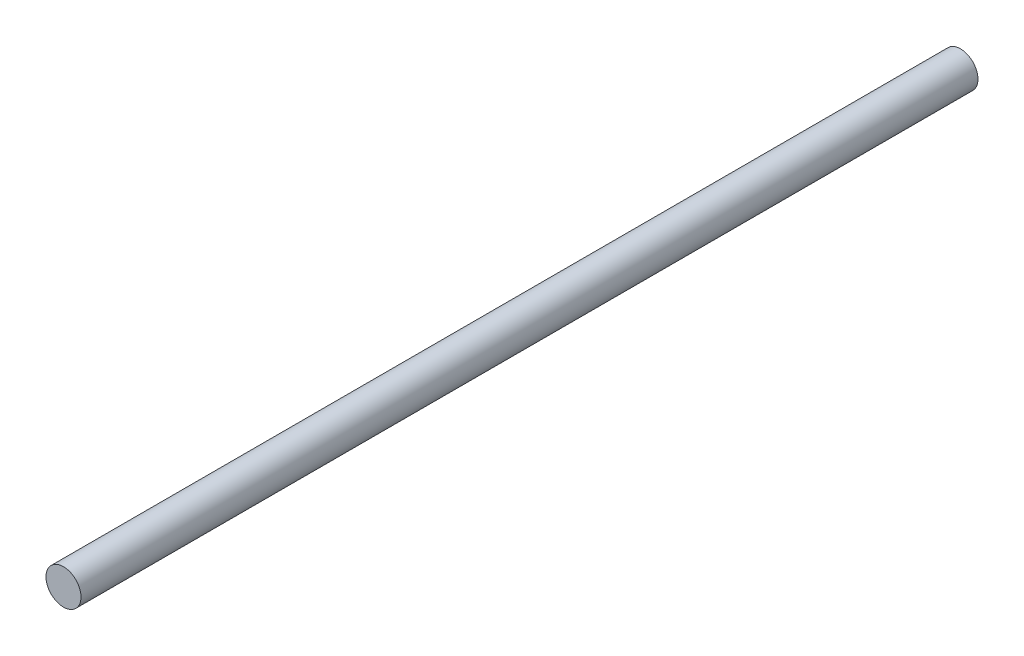
SolidWorks part; units mm, degrees
ref_plane "Front Plane" through (0, 0, 0) normal (0, 0, 1) x (1, 0, 0)
ref_plane "Top Plane" through (0, 0, 0) normal (0, 1, 0) x (1, 0, 0)
ref_plane "Right Plane" through (0, 0, 0) normal (1, 0, 0) x (0, 0, -1)
sketch "Sketch1" plane through (0, 0, 0) normal (0, 0, 1) x (1, 0, 0)
  circle A0 centre (0, 0) radius 3.9688
  dimension "D1" = 7.9375
extrude "Boss-Extrude1" add sketch "Sketch1" along normal blind 203.2
